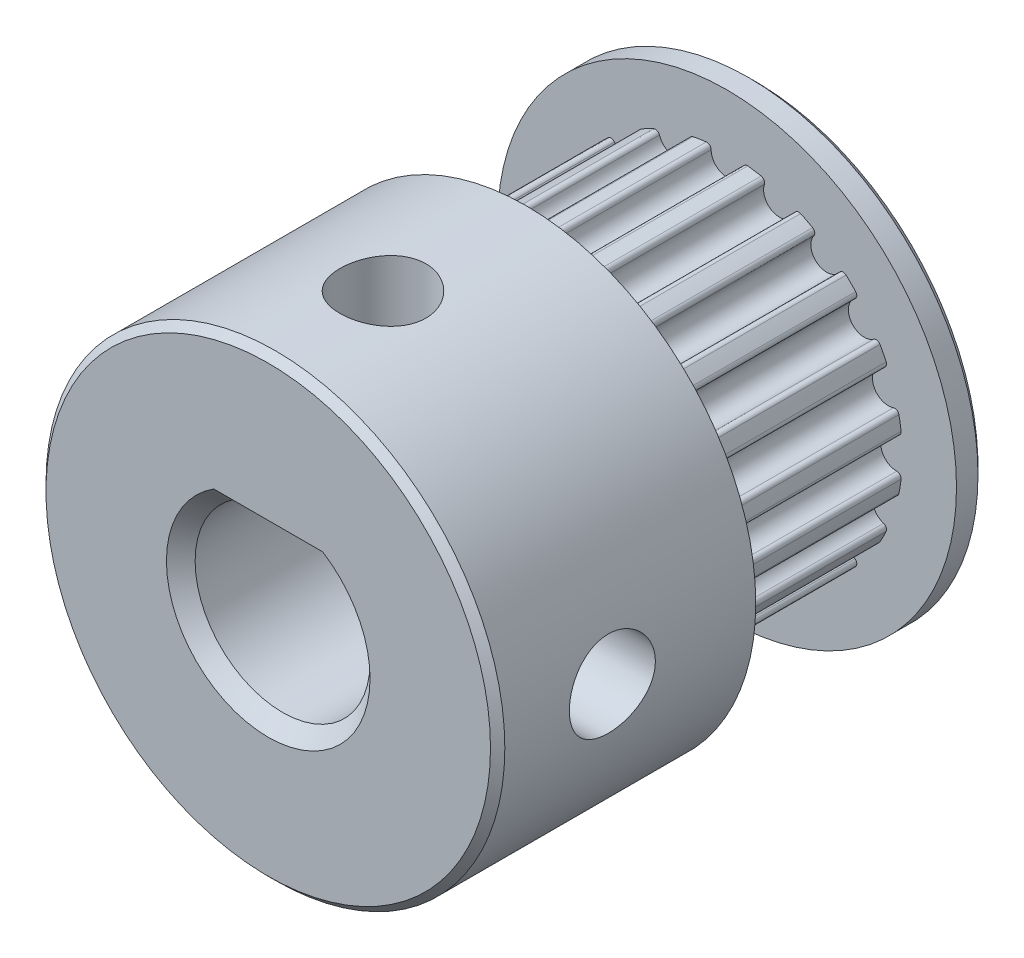
SolidWorks part; units mm, degrees
ref_plane "Front Plane" through (0, 0, 0) normal (0, 0, 1) x (1, 0, 0)
ref_plane "Top Plane" through (0, 0, 0) normal (0, 1, 0) x (1, 0, 0)
ref_plane "Right Plane" through (0, 0, 0) normal (1, 0, 0) x (0, 0, -1)
sketch "Sketch1" plane through (0, 0, 0) normal (0, 1, 0) x (1, 0, 0)
  line L0 (8, 1) -> (0, 1)
  line L1 (0, 1) -> (0, 0)
  line L2 (0, 0) -> (8, 0)
  line L3 (8, 0) -> (8, 1)
  line L4 (0, 1) -> (0, 0) construction
revolve "Revolve1" add sketch "Sketch1" angle 360 about L4
sketch "Sketch2" plane through (0, 0, 0) normal (0, 0, 1) x (1, 0, 0)
  arc A0 (0.5276, -6.0872) -> (-0.5276, -6.0872) centre (0, -5.915) ccw
  arc A1 (-0.5276, -6.0872) -> (-1.3792, -5.9523) centre (0, 0) cw
  arc A2 (-1.3792, -5.9523) -> (-2.3828, -5.6262) centre (-1.8278, -5.6255) ccw
  arc A3 (-2.3828, -5.6262) -> (-3.1511, -5.2348) centre (0, 0) cw
  arc A4 (-3.1511, -5.2348) -> (-4.0048, -4.6145) centre (-3.4767, -4.7853) ccw
  arc A5 (-4.0048, -4.6145) -> (-4.6145, -4.0048) centre (0, 0) cw
  arc A6 (-4.6145, -4.0048) -> (-5.2348, -3.1511) centre (-4.7853, -3.4767) ccw
  arc A7 (-5.2348, -3.1511) -> (-5.6262, -2.3828) centre (0, 0) cw
  arc A8 (-5.6262, -2.3828) -> (-5.9523, -1.3792) centre (-5.6255, -1.8278) ccw
  arc A9 (-5.9523, -1.3792) -> (-6.0872, -0.5276) centre (0, 0) cw
  arc A10 (-6.0872, -0.5276) -> (-6.0872, 0.5276) centre (-5.915, 0) ccw
  arc A11 (-6.0872, 0.5276) -> (-5.9523, 1.3792) centre (0, 0) cw
  arc A12 (-5.9523, 1.3792) -> (-5.6262, 2.3828) centre (-5.6255, 1.8278) ccw
  arc A13 (-5.6262, 2.3828) -> (-5.2348, 3.1511) centre (0, 0) cw
  arc A14 (-5.2348, 3.1511) -> (-4.6145, 4.0048) centre (-4.7853, 3.4767) ccw
  arc A15 (-4.6145, 4.0048) -> (-4.0048, 4.6145) centre (0, 0) cw
  arc A16 (-4.0048, 4.6145) -> (-3.1511, 5.2348) centre (-3.4767, 4.7853) ccw
  arc A17 (-3.1511, 5.2348) -> (-2.3828, 5.6262) centre (0, 0) cw
  arc A18 (-2.3828, 5.6262) -> (-1.3792, 5.9523) centre (-1.8278, 5.6255) ccw
  arc A19 (-1.3792, 5.9523) -> (-0.5276, 6.0872) centre (0, 0) cw
  arc A20 (-0.5276, 6.0872) -> (0.5276, 6.0872) centre (0, 5.915) ccw
  arc A21 (0.5276, 6.0872) -> (1.3792, 5.9523) centre (0, 0) cw
  arc A22 (1.3792, 5.9523) -> (2.3828, 5.6262) centre (1.8278, 5.6255) ccw
  arc A23 (2.3828, 5.6262) -> (3.1511, 5.2348) centre (0, 0) cw
  arc A24 (3.1511, 5.2348) -> (4.0048, 4.6145) centre (3.4767, 4.7853) ccw
  arc A25 (4.0048, 4.6145) -> (4.6145, 4.0048) centre (0, 0) cw
  arc A26 (4.6145, 4.0048) -> (5.2348, 3.1511) centre (4.7853, 3.4767) ccw
  arc A27 (5.2348, 3.1511) -> (5.6262, 2.3828) centre (0, 0) cw
  arc A28 (5.6262, 2.3828) -> (5.9523, 1.3792) centre (5.6255, 1.8278) ccw
  arc A29 (5.9523, 1.3792) -> (6.0872, 0.5276) centre (0, 0) cw
  arc A30 (6.0872, 0.5276) -> (6.0872, -0.5276) centre (5.915, 0) ccw
  arc A31 (6.0872, -0.5276) -> (5.9523, -1.3792) centre (0, 0) cw
  arc A32 (5.9523, -1.3792) -> (5.6262, -2.3828) centre (5.6255, -1.8278) ccw
  arc A33 (5.6262, -2.3828) -> (5.2348, -3.1511) centre (0, 0) cw
  arc A34 (5.2348, -3.1511) -> (4.6145, -4.0048) centre (4.7853, -3.4767) ccw
  arc A35 (4.6145, -4.0048) -> (4.0048, -4.6145) centre (0, 0) cw
  arc A36 (4.0048, -4.6145) -> (3.1511, -5.2348) centre (3.4767, -4.7853) ccw
  arc A37 (3.1511, -5.2348) -> (2.3828, -5.6262) centre (0, 0) cw
  arc A38 (2.3828, -5.6262) -> (1.3792, -5.9523) centre (1.8278, -5.6255) ccw
  arc A39 (1.3792, -5.9523) -> (0.5276, -6.0872) centre (0, 0) cw
extrude "Boss-Extrude1" add sketch "Sketch2" along normal blind 7
ref_plane "Plane1" through (0, 0, 7) normal (0, 0, -1) x (-1, 0, 0)
sketch "Esquisse2" plane through (0, 0, 7) normal (0, 0, 1) x (1, 0, 0)
  line L0 (-0.5276, 6.0872) -> (0.5276, 6.0872)
  line L1 (-0.45, 5.5902) -> (0.45, 5.5902)
  line L2 (0.5276, 6.0872) -> (0.45, 5.5902)
  line L3 (-0.5276, 6.0872) -> (-0.45, 5.5902)
  line L4 (0, 6.3918) -> (0, 5.0709) construction
  arc A0 (-0.5276, 6.0872) -> (0.5276, 6.0872) centre (0, 5.915) ccw construction
  dimension "D1" = 0.9
sketch "Sketch3" plane through (0, 0, 7) normal (0, 0, -1) x (-1, 0, 0)
  circle A0 centre (0, 0) radius 8
extrude "Boss-Extrude2" add sketch "Sketch3" against normal blind 9
sketch "Sketch4" plane through (0, 0, 16) normal (0, 0, 1) x (1, 0, 0)
  line L0 (1.7471, 2.5) -> (-1.7471, 2.5)
  arc A0 (-1.7471, 2.5) -> (1.7471, 2.5) centre (0, 0) ccw
extrude "Cut-Extrude1" cut sketch "Sketch4" against normal through all
hole_wizard "Ø3.0 Diameter Hole1" positions "3DSketch1" profile "Sketch5" hole size "Ø3.0" standard "ANSI Metric"
sketch3d "3DSketch1"
  point P0 (8, 0, 12)
sketch "Sketch5" plane through (8, 0, 12) normal (0, 1, 0) x (0, 0, -1)
  line L0 (0, 0) -> (0, 4.95)
  line L1 (0, 4.95) -> (1.5, 4.95)
  line L2 (1.5, 4.95) -> (1.5, 0)
  line L5 (1.5, 0) -> (0, 0)
  line L11 (0, -6.35) -> (0, 107.95) construction
  dimension "Thru Hole Dia." = 3
  dimension "Thru Hole Depth" = 4.95
hole_wizard "Ø3.0) Diameter Hole2" positions "Sketch7" profile "Sketch6" hole size "Ø3.0" standard "ANSI Metric"
sketch "Sketch7" plane through (0, 2.5, 0) normal (0, -1, 0) x (-1, 0, 0)
  point P0 (0, -12)
sketch "Sketch6" plane through (0, 2.5, 12) normal (1, 0, 0) x (0, 0, -1)
  line L0 (0, 0) -> (0, 5.5)
  line L1 (0, 5.5) -> (1.5, 5.5)
  line L2 (1.5, 5.5) -> (1.5, 0)
  line L5 (1.5, 0) -> (0, 0)
  line L11 (0, -6.35) -> (0, 107.95) construction
  dimension "Thru Hole Dia." = 3
  dimension "Thru Hole Depth" = 5.5
chamfer "Chamfer1" distance 0.25 angle 45 2 edges at (8, 0, 16) (8, 0, -1)
chamfer "Chamfer2" distance 0.5 angle 45 4 edges at (0, 2.5, -1) (0, -3.05, -1) (0, -3.05, 16) (0, 2.5, 16)
fillet "Fillet1" radius 0.15 40 edges at (-5.9523, 1.3792, 3.5) (-3.1511, -5.2348, 3.5) (-0.5276, 6.0872, 3.5) (1.3792, 5.9523, 3.5) (-5.6262, -2.3828, 3.5) (2.3828, 5.6262, 3.5) (-4.0048, 4.6145, 3.5) (0.5276, 6.0872, 3.5) (-1.3792, -5.9523, 3.5) (3.1511, 5.2348, 3.5) (-4.6145, -4.0048, 3.5) (4.0048, 4.6145, 3.5) (-6.0872, -0.5276, 3.5) (4.6145, 4.0048, 3.5) (-5.2348, 3.1511, 3.5) (5.2348, 3.1511, 3.5) (-2.3828, 5.6262, 3.5) (5.6262, 2.3828, 3.5) (-0.5276, -6.0872, 3.5) (5.9523, 1.3792, 3.5) (-2.3828, -5.6262, 3.5) (6.0872, 0.5276, 3.5) (-4.0048, -4.6145, 3.5) (6.0872, -0.5276, 3.5) (-5.2348, -3.1511, 3.5) (5.9523, -1.3792, 3.5) (-5.9523, -1.3792, 3.5) (5.6262, -2.3828, 3.5) (-6.0872, 0.5276, 3.5) (5.2348, -3.1511, 3.5) (-5.6262, 2.3828, 3.5) (4.6145, -4.0048, 3.5) (-4.6145, 4.0048, 3.5) (4.0048, -4.6145, 3.5) (-3.1511, 5.2348, 3.5) (2.3828, -5.6262, 3.5) (-1.3792, 5.9523, 3.5) (1.3792, -5.9523, 3.5) (0.5276, -6.0872, 3.5) (3.1511, -5.2348, 3.5)
sketch "Esquisse1" plane through (0, 0, 7) normal (0, 0, -1) x (-1, 0, 0)
  circle A0 centre (0, 0) radius 6.11
